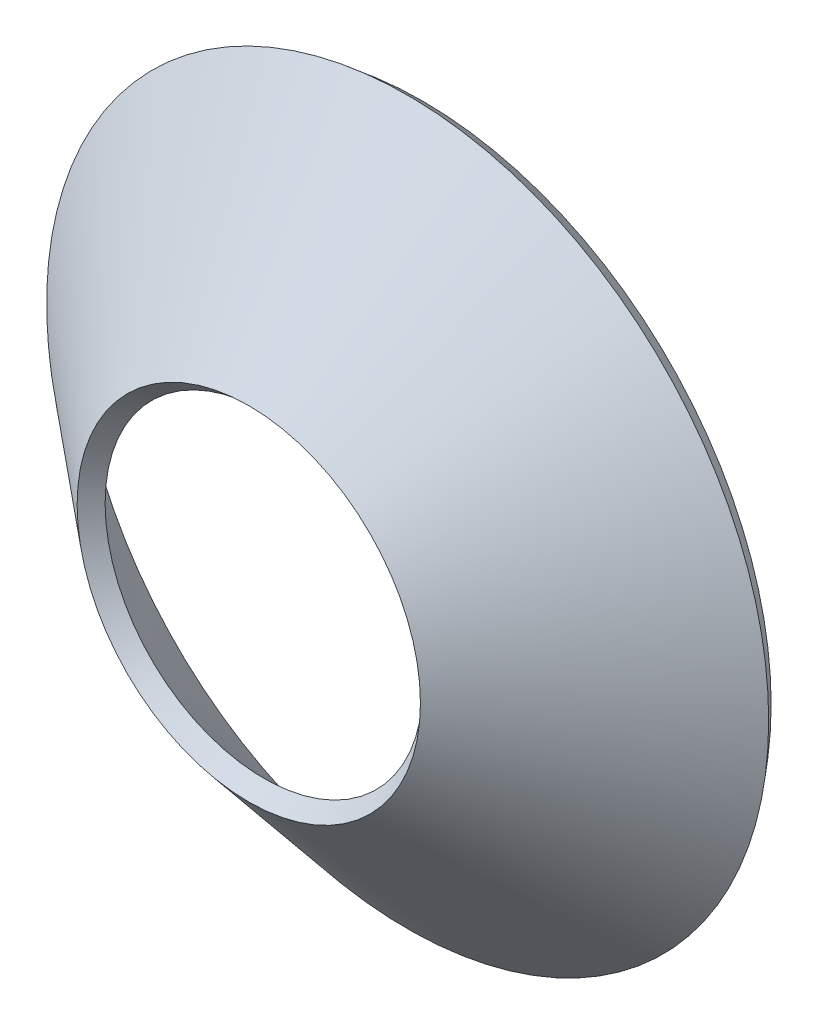
SolidWorks part; units mm, degrees
ref_plane "Front Plane" through (0, 0, 0) normal (1, 0, 0) x (0, 1, 0)
ref_plane "Top Plane" through (0, 0, 0) normal (0, 0, 1) x (0, 1, 0)
ref_plane "Right Plane" through (0, 0, 0) normal (0, 1, 0) x (-1, 0, 0)
sketch "Sketch1" plane through (0, 0, 0) normal (1, 0, 0) x (0, 1, 0)
  line L0 (25.4, 25.4) -> (55.6705, 0)
  line L1 (55, 0) -> (-55, 0) construction
  line L2 (0, -55) -> (0, 55) construction
  dimension "D1" = 40
  dimension "D2" = 25.4
  dimension "D3" = 25.4
ref_axis "Axis1" through (0, 0, 26.67) along (0, 0, -1)
revolve "Revolve-Thin1" add sketch "Sketch1" angle 360 about axis through (0, 0, 26.67) along (0, 0, -1) wall 3.175
